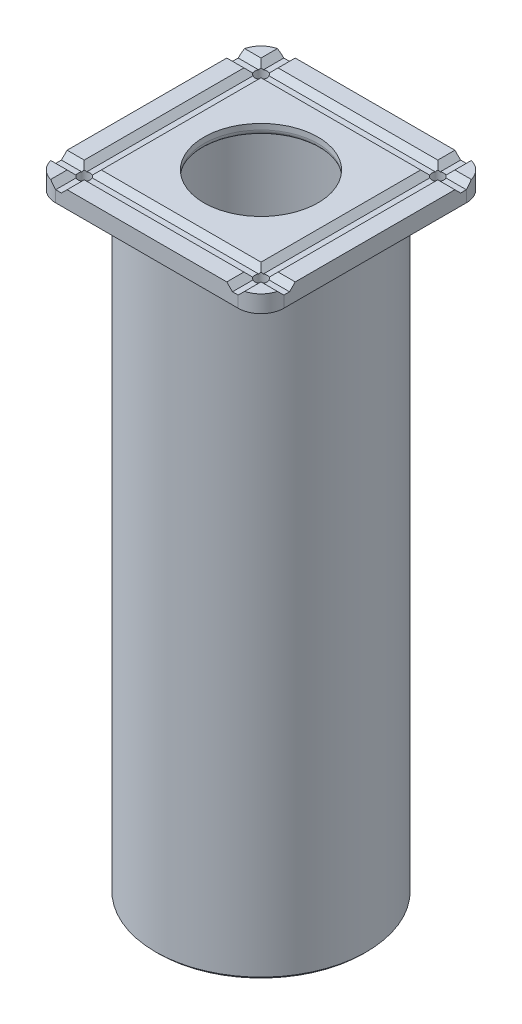
SolidWorks part; units mm, degrees
ref_plane "Front Plane" through (0, 0, 0) normal (0, 0, 1) x (1, 0, 0)
ref_plane "Top Plane" through (0, 0, 0) normal (0, 1, 0) x (1, 0, 0)
ref_plane "Right Plane" through (0, 0, 0) normal (1, 0, 0) x (0, 0, -1)
sketch "Sketch1" plane through (0, 0, 0) normal (0, 1, 0) x (1, 0, 0)
  circle A0 centre (0, 0) radius 16.5
  circle A1 centre (0, 0) radius 18.5
  dimension "D1" = 2
  dimension "D2" = 33
extrude "Boss-Extrude1" add sketch "Sketch1" along normal blind 108
sketch "Sketch2" plane through (0, 108, 0) normal (0, 1, 0) x (1, 0, 0)
  circle A0 centre (0, 0) radius 18.5 construction
  circle A1 centre (0, 0) radius 18.5
extrude "Boss-Extrude2" add sketch "Sketch2" along normal blind 2
sketch "Sketch3" plane through (0, 110, 0) normal (0, 1, 0) x (1, 0, 0)
  circle A0 centre (0, 0) radius 10
  dimension "D1" = 20
extrude "Cut-Extrude1" cut sketch "Sketch3" against normal through all
sketch "Sketch4" plane through (0, 110, 0) normal (0, 1, 0) x (1, 0, 0)
  line L1 (20, -20) -> (-20, -20)
  line L2 (20, -20) -> (20, 20)
  line L3 (20, 20) -> (-20, 20)
  line L4 (-20, -20) -> (-20, 20)
  line L5 (20, -20) -> (-20, 20) construction
  line L6 (20, 20) -> (-20, -20) construction
  circle A0 centre (0, 0) radius 18.5 construction
  circle A1 centre (0, 0) radius 18.5
  dimension "D1" = 40
extrude "Boss-Extrude3" add sketch "Sketch4" against normal blind 3
fillet "Fillet1" radius 4 4 edges at (-20, 108.5, -20) (20, 108.5, -20) (-20, 108.5, 20) (20, 108.5, 20)
sketch "Sketch5" plane through (0, 0, 20) normal (0, 0, 1) x (1, 0, 0)
  line L0 (14, 110) -> (17, 110)
  line L1 (-16, 110) -> (16, 110) construction
  line L2 (17, 110) -> (16, 109)
  line L3 (16, 109) -> (15, 109)
  line L4 (15, 109) -> (14, 110)
  point P7 (0, 110)
  dimension "D1" = 45
  dimension "D2" = 1
  dimension "D3" = 3
  dimension "D4" = 14
extrude "Cut-Extrude2" cut sketch "Sketch5" against normal through all
mirror "Mirror1" about plane through (0, 0, 0) normal (1, 0, 0) of "Cut-Extrude2"
pattern_circular "CirPattern1" count 2 every 90 about axis through (0, 0, 0) along (0, 1, 0) of "Cut-Extrude2", "Mirror1"
sketch "Sketch6" plane through (0, 107, 0) normal (0, -1, 0) x (1, 0, 0)
  line L1 (15.5, -15.5) -> (-15.5, -15.5) construction
  line L2 (15.5, -15.5) -> (15.5, 15.5) construction
  line L3 (15.5, 15.5) -> (-15.5, 15.5) construction
  line L4 (-15.5, -15.5) -> (-15.5, 15.5) construction
  line L5 (15.5, -15.5) -> (-15.5, 15.5) construction
  line L6 (15.5, 15.5) -> (-15.5, -15.5) construction
  circle A0 centre (15.5, 15.5) radius 1.05
  circle A1 centre (-15.5, 15.5) radius 1.05
  circle A2 centre (-15.5, -15.5) radius 1.05
  circle A3 centre (15.5, -15.5) radius 1.05
  point P0 (0, 0)
  dimension "D2" = 2.1
  dimension "D1" = 31
extrude "Cut-Extrude3" cut sketch "Sketch6" against normal through all
fillet "Fillet2" radius 1 2 edges at (0, 107, 18.5) (0, 108, 10)
chamfer "Chamfer1" distance 0.5 angle 45 2 edges at (0, 0, 18.5) (0, 0, 16.5)
